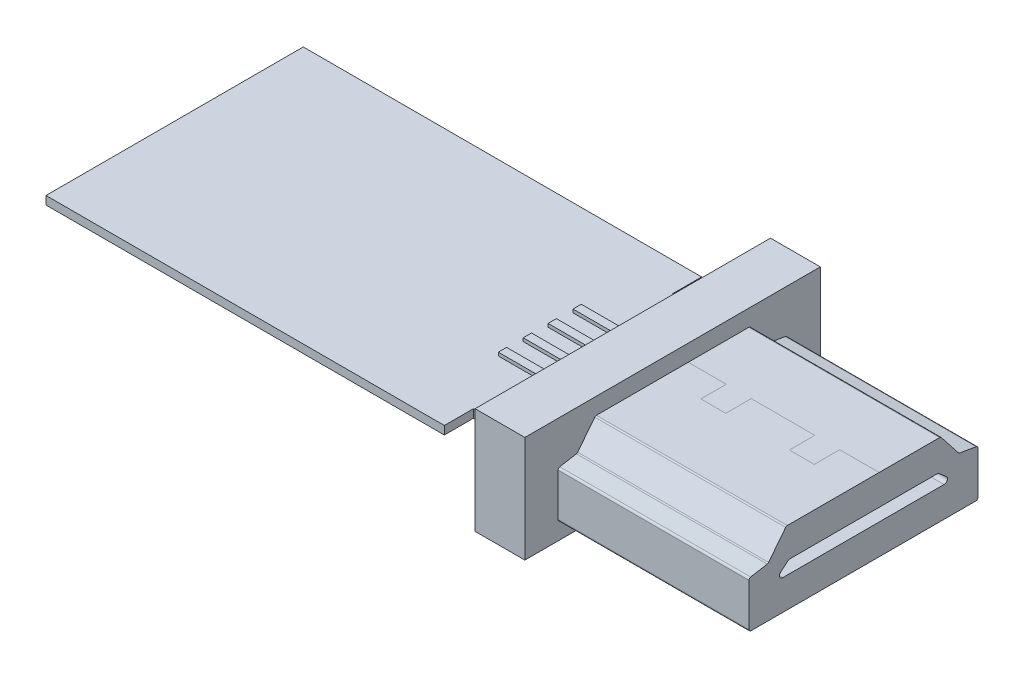
SolidWorks part; units mm, degrees
ref_plane "Front Plane" through (0, 0, 0) normal (0, 0, 1) x (1, 0, 0)
ref_plane "Top Plane" through (0, 0, 0) normal (0, 1, 0) x (1, 0, 0)
ref_plane "Right Plane" through (0, 0, 0) normal (1, 0, 0) x (0, 0, -1)
sketch "Sketch1" plane through (0, 0, 0) normal (1, 0, 0) x (0, 0, -1)
  line L0 (0, 2.8) -> (1.1527, 3.0006)
  line L1 (0, 0) -> (13.8, 0)
  line L2 (0, 0) -> (0, 2.8)
  line L3 (2.25, 4.4) -> (11.55, 4.4)
  line L4 (13.8, 0) -> (13.8, 2.8)
  line L5 (1.1527, 3.0006) -> (2.25, 4.4)
  line L6 (6.9, 0) -> (6.9, 7.0139) construction
  line L7 (13.8, 2.8) -> (12.6473, 3.0006)
  line L8 (12.6473, 3.0006) -> (11.55, 4.4)
  dimension "D1" = 13.8
  dimension "D2" = 9.3
  dimension "D3" = 2.8
  dimension "D4" = 4.4
  dimension "D5" = 9.87
  dimension "D6" = 1.17
extrude "Boss-Extrude1" add sketch "Sketch1" along normal blind 11.5
sketch "Sketch2" plane through (0, 0, 0) normal (-1, 0, 0) x (0, 0, 1)
  line L0 (0, 0) -> (-13.8, 0) construction
  line L1 (-15.8, 5.4) -> (2, 5.4)
  line L2 (-15.8, 5.4) -> (-15.8, -1)
  line L3 (-15.8, -1) -> (2, -1)
  line L4 (2, 5.4) -> (2, -1)
  line L5 (-11.55, 4.4) -> (-2.25, 4.4) construction
  line L6 (0, 2.8) -> (0, 0) construction
  point P6 (-6.9, 0)
  point P7 (-6.9, -1)
  dimension "D1" = 1
  dimension "D2" = 1
  dimension "D3" = 2
extrude "Boss-Extrude2" add sketch "Sketch2" along normal blind 3
ref_plane "Plane1" through (0, 2.2, 0) normal (0, 1, 0) x (1, 0, 0)
sketch "Sketch3" plane through (0, 2.2, 0) normal (0, 1, 0) x (1, 0, 0)
  line L0 (-3, 12.9) -> (-6, 12.9)
  line L1 (-3, -2) -> (-3, 15.8) construction
  line L2 (-6, 12.9) -> (-6, 14.65)
  line L3 (-6, 14.65) -> (-30, 14.65)
  line L4 (-30, 14.65) -> (-30, -0.85)
  line L5 (-30, -0.85) -> (-6, -0.85)
  line L6 (-6, -0.85) -> (-6, 0.9)
  line L7 (-6, 0.9) -> (-3, 0.9)
  line L8 (-3, 12.9) -> (-3, 0.9)
  point P9 (-30, 6.9)
  point P11 (-3, 6.9)
  dimension "D1" = 30
  dimension "D2" = 12
  dimension "D3" = 24
  dimension "D4" = 15.5
extrude "Boss-Extrude3" add sketch "Sketch3" along normal mid plane 0.5
sketch "Sketch4" plane through (0, 2.45, 0) normal (0, 1, 0) x (1, 0, 0)
  line L0 (-3, 0.9) -> (-3, 12.9) construction
  line L1 (-8, 9.4) -> (-3, 9.4)
  line L2 (-8, 9.4) -> (-8, 8.9)
  line L3 (-8, 8.9) -> (-3, 8.9)
  line L4 (-3, 9.4) -> (-3, 8.9)
  line L5 (-3, 7.9) -> (-3, 7.4)
  line L6 (-8, 7.4) -> (-3, 7.4)
  line L7 (-8, 7.9) -> (-8, 7.4)
  line L8 (-8, 7.9) -> (-3, 7.9)
  line L9 (-3, 6.4) -> (-3, 5.9)
  line L10 (-8, 5.9) -> (-3, 5.9)
  line L11 (-8, 6.4) -> (-8, 5.9)
  line L12 (-8, 6.4) -> (-3, 6.4)
  line L13 (-8, 4.4) -> (-3, 4.4)
  line L14 (-8, 4.9) -> (-3, 4.9)
  line L15 (-8, 4.9) -> (-8, 4.4)
  line L16 (-3, 4.9) -> (-3, 4.4)
  line L17 (-3, 12.9) -> (-6, 12.9) construction
  line L18 (-6, 0.9) -> (-3, 0.9) construction
  dimension "D1" = 5
  dimension "D2" = 0.5
  dimension "D3" = 0.5
  dimension "D4" = 0.5
  dimension "D5" = 0.5
  dimension "D6" = 3.5
  dimension "D7" = 3.5
  dimension "D8" = 1
  dimension "D9" = 1
extrude "Boss-Extrude4" add sketch "Sketch4" along normal blind 0.2
ref_plane "Plane2" through (0, 2.2, 0) normal (0, 1, 0) x (1, 0, 0)
mirror "Mirror1" about plane through (0, 2.2, 0) normal (0, 1, 0) of "Boss-Extrude4"
fillet "Fillet1" radius 0.125 8 edges at (5.75, 4.4, -11.55) (5.75, 3.0006, -12.6473) (5.75, 2.8, -13.8) (5.75, 0, -13.8) (5.75, 0, 0) (5.75, 2.8, 0) (5.75, 3.0006, -1.1527) (5.75, 4.4, -2.25)
sketch "Sketch5" plane through (11.5, 0, 0) normal (1, 0, 0) x (0, 0, -1)
  line L0 (2.4, 2.5825) -> (1.5, 1.8175)
  line L1 (1.5, 1.8175) -> (12.3, 1.8175)
  line L2 (12.3, 1.8175) -> (11.4, 2.5825)
  line L3 (11.4, 2.5825) -> (2.4, 2.5825)
  line L4 (0.125, 0) -> (13.675, 0) construction
  line L5 (11.4892, 4.4) -> (2.3108, 4.4) construction
  line L7 (6.9, 2.5825) -> (6.9, 1.8175) construction
  line L8 (-2, -1) -> (-2, 5.4) construction
  point P2 (6.9, 1.8175)
  point P7 (6.9, 0)
  point P8 (6.9, 2.5825)
  point P11 (6.9, 4.4)
  point P12 (6.9, 2.2)
  point P17 (-2, 2.2)
  dimension "D1" = 10.8
  dimension "D2" = 0.765
  dimension "D3" = 9
extrude "Cut-Extrude1" cut sketch "Sketch5" against normal offset from surface (6.5 mm away) 5 up to face at (0, 2.2, -6.9)
fillet "Fillet2" radius 0.2 4 edges at (8.25, 2.5825, -2.4) (8.25, 1.8175, -1.5) (8.25, 2.5825, -11.4) (8.25, 1.8175, -12.3)
sketch "Sketch7" plane through (0, 4.4, 0) normal (0, 1, 0) x (1, 0, 0)
  line L0 (0, 7.8441) -> (2.2902, 7.8441)
  line L1 (0, -2) -> (0, 15.8) construction
  line L2 (2.2902, 7.8441) -> (2.2902, 6.3126)
  line L3 (2.2902, 6.3126) -> (3.7902, 6.3126)
  line L4 (3.7902, 6.3126) -> (3.7902, 7.8441)
  line L5 (3.7902, 7.8441) -> (7.6245, 7.8441)
  line L6 (7.6245, 7.8441) -> (7.6245, 6.3137)
  line L7 (7.6245, 6.3137) -> (9.1245, 6.3137)
  line L8 (9.1245, 6.3137) -> (9.1245, 7.8441)
  line L9 (9.1245, 7.8441) -> (11.5, 7.8441)
  line L10 (11.5, 11.4892) -> (11.5, 2.3108) construction
  line L11 (11.5, 11.4892) -> (0, 11.4892) construction
  dimension "D1" = 1.5
  dimension "D2" = 2.3755
  dimension "D3" = 3.6451
  dimension "D4" = 7.7098
  dimension "D5" = 5.1755
  dimension "D6" = 5.1766
split line "Split Line1"
